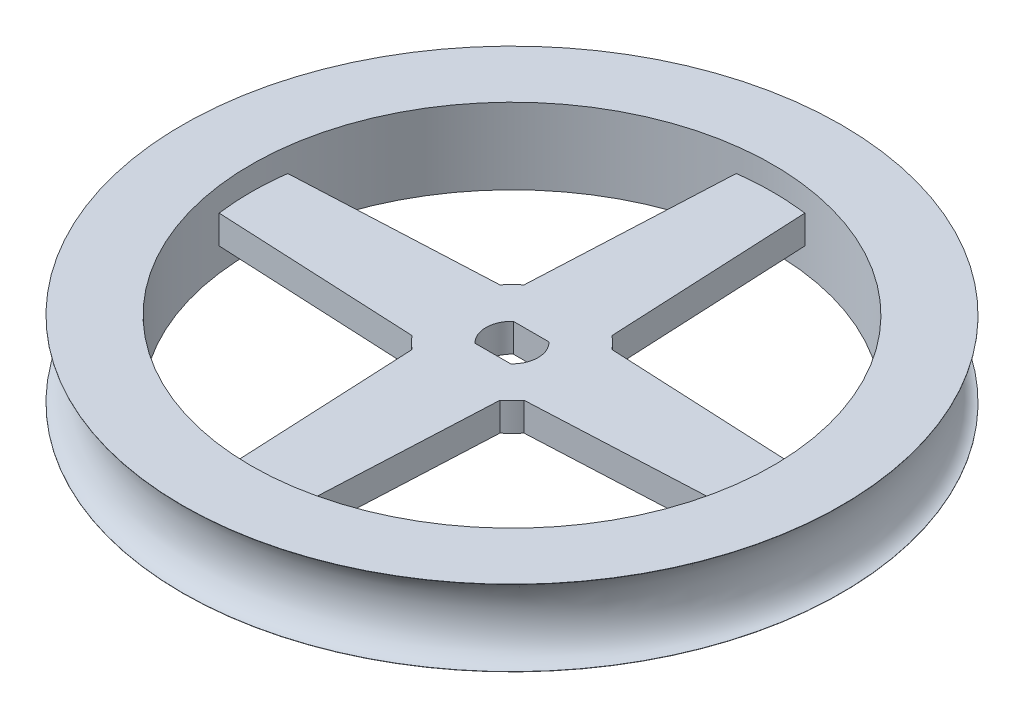
SolidWorks part; units mm, degrees
ref_plane "Front Plane" through (0, 0, 0) normal (0, 0, 1) x (1, 0, 0)
ref_plane "Top Plane" through (0, 0, 0) normal (0, 1, 0) x (1, 0, 0)
ref_plane "Right Plane" through (0, 0, 0) normal (1, 0, 0) x (0, 0, -1)
sketch "Sketch1" plane through (0, 0, 0) normal (0, 1, 0) x (1, 0, 0)
  circle A0 centre (0, 0) radius 35
  circle A1 centre (0, 0) radius 27.5
  dimension "D1" = 70
  dimension "D2" = 55
extrude "Boss-Extrude3" add sketch "Sketch1" along normal mid plane 8
sketch "Sketch4" plane through (0, 0, 0) normal (1, 0, 0) x (0, 0, -1)
  line L0 (-35, 4) -> (-35, -4) construction
  line L1 (-35, 4) -> (-35, -4)
  line L2 (0, 4.5685) -> (0, -4.8088) construction
  line L3 (38.5, 0) -> (-38.5, 0) construction
  line L4 (-35, 4) -> (-35, -4) construction
  line L5 (35, 4) -> (-35, 4) construction
  ellipse E0 centre (-35, 0) end of major axis (-35, 4) minor radius 2.4636 (-32.5364, 0) -> (-35, 4) ccw
  ellipse E1 centre (-35, 0) end of major axis (-35, -4) minor radius 2.4636 (-32.5364, 0) -> (-35, -4) cw
  point P4 (0, 0)
  point P16 (-35, 3.9996)
  point P21 (-35, 3.4137)
  point P24 (-35, 4)
  point P27 (0, 0)
  point P28 (-32.5364, 0)
revolve "Cut-Revolve2" cut sketch "Sketch4" angle 360 about L2
sketch "Sketch5" plane through (0, 0, 0) normal (0, 1, 0) x (1, 0, 0)
  line L0 (-3.6149, 27.2614) -> (-4.6314, 5.8992)
  line L1 (3.6149, 27.2614) -> (4.6314, 5.8992)
  line L2 (27.2614, -3.6149) -> (5.8992, -4.6314)
  line L3 (27.2614, 3.6149) -> (5.8992, 4.6314)
  line L4 (-3.6149, -27.2614) -> (-4.6314, -5.8992)
  line L5 (3.6149, -27.2614) -> (4.6314, -5.8992)
  line L6 (-27.2614, 3.6149) -> (-5.8992, 4.6314)
  line L7 (-27.2614, -3.6149) -> (-5.8992, -4.6314)
  line L8 (-1.875, 2.0117) -> (1.875, 2.0117)
  line L9 (-1.875, -2.0117) -> (1.875, -2.0117)
  arc A0 (-1.875, 2.0117) -> (-1.875, -2.0117) centre (0, 0) ccw
  arc A1 (-4.6314, 5.8992) -> (-5.8992, 4.6314) centre (0, 0) ccw
  arc A2 (27.2614, -3.6149) -> (27.2614, 3.6149) centre (0, 0) ccw
  arc A3 (3.6149, 27.2614) -> (-3.6149, 27.2614) centre (0, 0) ccw
  arc A4 (-3.6149, -27.2614) -> (3.6149, -27.2614) centre (0, 0) ccw
  arc A5 (-27.2614, 3.6149) -> (-27.2614, -3.6149) centre (0, 0) ccw
  arc A6 (-5.8992, -4.6314) -> (-4.6314, -5.8992) centre (0, 0) ccw
  arc A7 (4.6314, -5.8992) -> (5.8992, -4.6314) centre (0, 0) ccw
  arc A8 (5.8992, 4.6314) -> (4.6314, 5.8992) centre (0, 0) ccw
  arc A9 (1.875, -2.0117) -> (1.875, 2.0117) centre (0, 0) ccw
  circle A10 centre (0, 0) radius 27.5 construction
  point P22 (0, 0)
  dimension "D1" = 5.5
  dimension "D2" = 15
  dimension "D4" = 3.75
  dimension "D5" = 3.75
  dimension "D6" = 21.3622
  dimension "D7" = 21.3622
  dimension "D3" = 4
extrude "Boss-Extrude4" add sketch "Sketch5" along normal mid plane 3 separate body
sketch "Sketch6" plane through (0, 0, 0) normal (0, 0, 1) x (1, 0, 0)
  line L0 (0, 8.7925) -> (0, -8.7471) construction
  line L1 (-36.0159, 5.2585) -> (-34.7396, 5.2585)
  line L2 (-36.0159, 5.2585) -> (-36.0159, -4.6163)
  line L3 (-36.0159, -4.6163) -> (-34.7396, -4.6163)
  line L4 (-34.7396, 5.2585) -> (-34.7396, -4.6163)
revolve "Cut-Revolve3" cut sketch "Sketch6" angle 360 about L0
